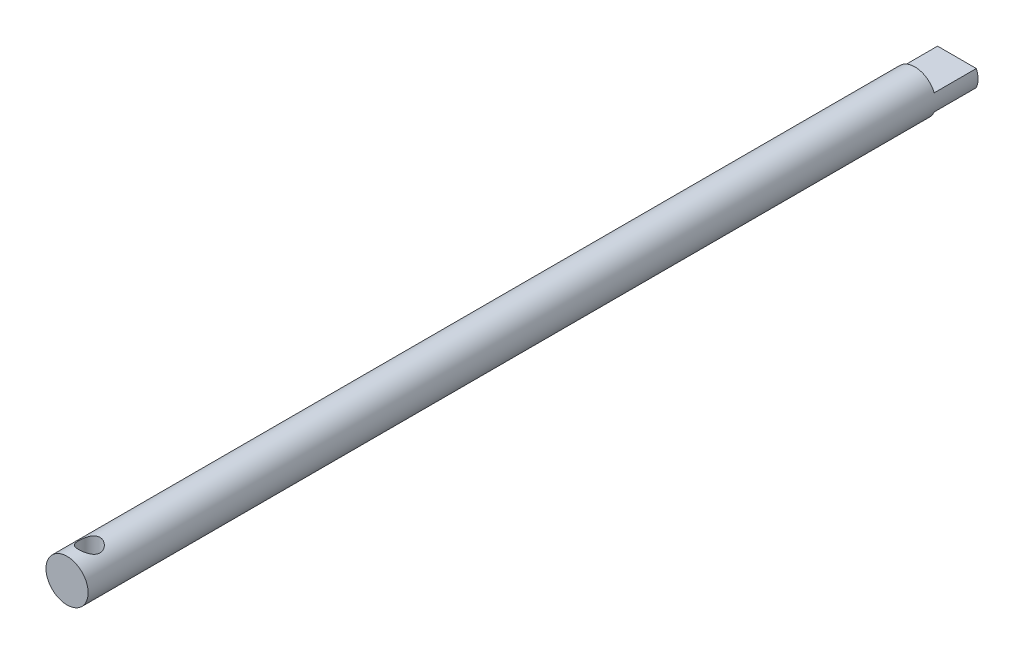
SolidWorks part; units mm, degrees
ref_plane "Front Plane" through (0, 0, 0) normal (0, 0, 1) x (1, 0, 0)
ref_plane "Top Plane" through (0, 0, 0) normal (0, 1, 0) x (1, 0, 0)
ref_plane "Right Plane" through (0, 0, 0) normal (1, 0, 0) x (0, 0, -1)
sketch "Sketch1" plane through (0, 0, 0) normal (0, 0, 1) x (1, 0, 0)
  circle A0 centre (0, 0) radius 3.175
  dimension "D1" = 6.35
extrude "Boss-Extrude1" add sketch "Sketch1" along normal blind 134
sketch "Sketch2" plane through (0, 0, 0) normal (0, 0, -1) x (-1, 0, 0)
  line L0 (-2.9186, 1.25) -> (2.9186, 1.25)
  line L1 (-2.9186, -1.25) -> (2.9186, -1.25)
  line L2 (0, 1.25) -> (0, -1.25) construction
  circle A0 centre (0, 0) radius 3.175 construction
  point P8 (0, 0)
  circle M4 centre (0, 0) radius 3.175
  dimension "D1" = 2.5
extrude "Cut-Extrude1" cut sketch "Sketch2" against normal blind 6.34 contours L0 M4 | L1 M4
ref_plane "Plane1" through (0, 3.175, 0) normal (0, 1, 0) x (1, 0, 0)
sketch "Sketch5" plane through (0, 3.175, 0) normal (0, 1, 0) x (1, 0, 0)
  line L0 (-3.175, -134) -> (3.175, -134) construction
  line L1 (-3.175, -134) -> (3.175, -134) construction
  circle A0 centre (0, -130.65) radius 1.6
  point P4 (0, 0)
  point P5 (0, -134)
  point P6 (0, -150.6823)
  dimension "D2" = 3.2
  dimension "D1" = 3.35
extrude "Cut-Extrude2" cut sketch "Sketch5" against normal through all
